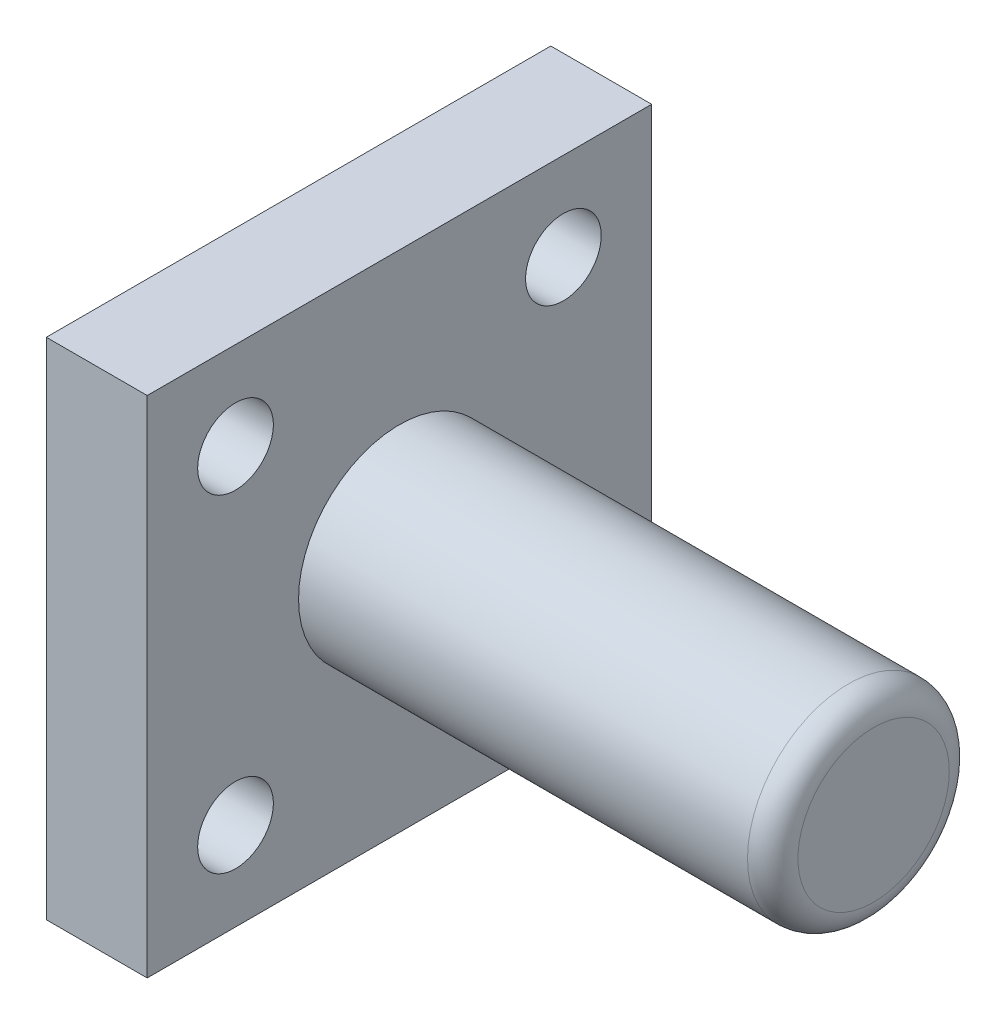
SolidWorks part; units mm, degrees
ref_plane "Front Plane" through (0, 0, 0) normal (0, 0, 1) x (1, 0, 0)
ref_plane "Top Plane" through (0, 0, 0) normal (0, 1, 0) x (1, 0, 0)
ref_plane "Right Plane" through (0, 0, 0) normal (1, 0, 0) x (0, 0, -1)
sketch "Sketch1" plane through (0, 0, 0) normal (1, 0, 0) x (0, 0, -1)
  line L1 (-10, -10) -> (10, -10)
  line L2 (-10, -10) -> (-10, 10)
  line L3 (-10, 10) -> (10, 10)
  line L4 (10, -10) -> (10, 10)
  line L5 (-10, -10) -> (10, 10) construction
  line L6 (-10, 10) -> (10, -10) construction
  point P0 (0, 0)
  dimension "D1" = 20
  dimension "D2" = 20
extrude "Boss-Extrude1" add sketch "Sketch1" along normal blind 4
sketch "Sketch2" plane through (4, 0, 0) normal (1, 0, 0) x (0, 0, -1)
  circle A0 centre (0, 0) radius 4
  dimension "D1" = 8
extrude "Boss-Extrude2" add sketch "Sketch2" along normal blind 18.8
hole_wizard "Ø3.0mm Dowel Hole1" positions "Sketch5" profile "Sketch3" hole size "Ø3.0" standard "ANSI Metric" end condition through all
sketch "Sketch5" plane through (0, 0, 0) normal (-1, 0, 0) x (0, 0, 1)
  line L0 (-10, -10) -> (-10, 10) construction
  line L1 (10, 10) -> (10, -10) construction
  line L2 (10, -10) -> (-10, -10) construction
  line L3 (-10, 10) -> (10, 10) construction
  point P0 (-6.5, -6.5)
  point P2 (-6.5, 6.5)
  point P4 (6.5, 6.5)
  point P6 (6.5, -6.5)
  dimension "D1" = 3.5
  dimension "D2" = 3.5
  dimension "D3" = 3.5
  dimension "D4" = 3.5
  dimension "D5" = 3.5
  dimension "D6" = 3.5
  dimension "D7" = 3.5
  dimension "D8" = 3.5
sketch "Sketch3" plane through (0, -6.5, -6.5) normal (0, 1, 0) x (0, 0, 1)
  line L0 (0, 0) -> (0, 22.8)
  line L1 (0, 22.8) -> (1.5, 22.8)
  line L2 (1.5, 22.8) -> (1.5, 0)
  line L5 (1.5, 0) -> (0, 0)
  line L11 (0, -6.35) -> (0, 107.95) construction
  dimension "Thru Hole Dia." = 3
  dimension "Thru Hole Depth" = 22.8
fillet "Fillet1" radius 1 1 edges at (22.8, 0, -4)
